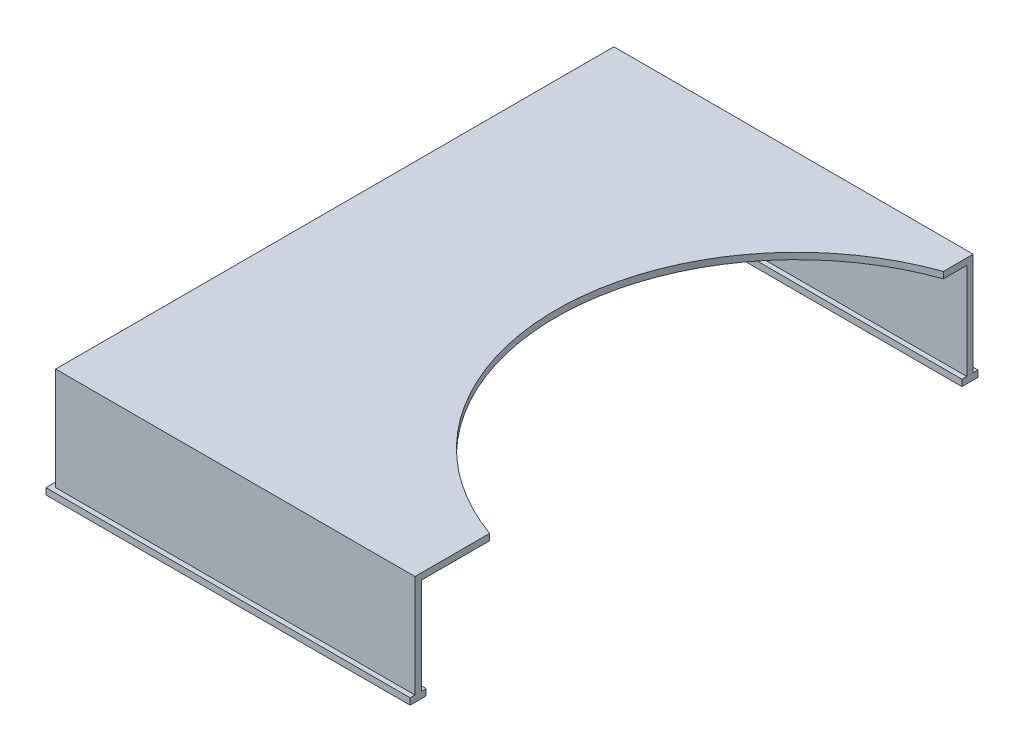
SolidWorks part; units mm, degrees
ref_plane "前视基准面" through (0, 0, 0) normal (0, 0, 1) x (1, 0, 0)
ref_plane "上视基准面" through (0, 0, 0) normal (0, 1, 0) x (1, 0, 0)
ref_plane "右视基准面" through (0, 0, 0) normal (1, 0, 0) x (0, 0, -1)
other "Configuration Table"
sketch "草图1" plane through (0, 0, 0) normal (0, 1, 0) x (1, 0, 0)
  line L1 (0, 0) -> (220, 0)
  line L2 (0, 0) -> (0, -170)
  line L3 (0, -170) -> (220, -170)
  line L4 (220, 0) -> (220, -170)
  line L9 (-2, 2) -> (222, 2)
  line L10 (-2, 2) -> (-2, -172)
  line L11 (-2, -172) -> (222, -172)
  line L12 (222, 2) -> (222, -172)
  point P4 (-2, 0)
  point P5 (0, 2)
  point P7 (222, -170)
  point P8 (220, -172)
  dimension "D1" = 220
  dimension "D2" = 170
  dimension "D3" = 2
  dimension "D4" = 2
  dimension "D5" = 2
  dimension "D6" = 2
extrude "凸台-拉伸1" add sketch "草图1" along normal blind 32
sketch "草图2" plane through (0, 0, 0) normal (0, 1, 0) x (1, 0, 0)
  line L0 (220, -170) -> (220, 0) construction
  line L1 (0, -170) -> (220, -170) construction
  line L2 (0, 0) -> (0, -170) construction
  line L3 (220, 0) -> (0, 0) construction
  line L14 (-3.5, 3.5) -> (223.5, 3.5)
  line L15 (-3.5, 3.5) -> (-3.5, -173.5)
  line L16 (-3.5, -173.5) -> (223.5, -173.5)
  line L17 (223.5, 3.5) -> (223.5, -173.5)
  line L18 (218.5, -168.5) -> (1.5, -168.5)
  line L19 (218.5, -168.5) -> (218.5, -1.5)
  line L20 (218.5, -1.5) -> (1.5, -1.5)
  line L21 (1.5, -168.5) -> (1.5, -1.5)
  point P0 (-3.5, 2)
  point P1 (-2, 3.5)
  point P2 (222, -173.5)
  point P3 (223.5, -172)
  point P4 (220, -168.5)
  point P5 (218.5, -170)
  point P8 (0, -1.5)
  point P11 (1.5, 0)
  point P14 (0, 0)
  point P17 (220, -170)
  point P18 (-2, 2)
  point P19 (222, -172)
  dimension "D1" = 1.5
  dimension "D2" = 1.5
  dimension "D3" = 1.5
  dimension "D4" = 1.5
  dimension "D5" = 1.5
  dimension "D6" = 1.5
  dimension "D7" = 1.5
  dimension "D8" = 1.5
extrude "凸台-拉伸2" add sketch "草图2" against normal blind 2
ref_plane "基准面1" through (0, 32, 0) normal (0, 1, 0) x (1, 0, 0)
sketch "草图3" plane through (0, 32, 0) normal (0, 1, 0) x (1, 0, 0)
  line L0 (-2, 2) -> (-2, -172) construction
  line L1 (222, -172) -> (222, 2) construction
  line L7 (-2, 2) -> (220, 2)
  line L8 (-2, 2) -> (-2, -170)
  line L9 (-2, -170) -> (220, -170)
  line L10 (220, 2) -> (220, -170)
  circle A0 centre (135, -78) radius 75
  point P0 (-2, -78)
  point P1 (222, -78)
  point P5 (210, -78)
  point P8 (60, -78)
  point P9 (135, -78)
  dimension "D1" = 80
  dimension "D2" = 12
  dimension "D3" = 62
  dimension "D4" = 75
extrude "凸台-拉伸3" add sketch "草图3" against normal blind 2
sketch "草图4" plane through (0, 32, 0) normal (0, 1, 0) x (1, 0, 0)
  line L0 (223.5, 3.5) -> (-3.5, 3.5) construction
  line L2 (110, 3.5) -> (223.5, 3.5)
  line L3 (110, 3.5) -> (110, -173.5)
  line L4 (110, -173.5) -> (223.5, -173.5)
  line L5 (223.5, 3.5) -> (223.5, -173.5)
  point P0 (110, 3.5)
extrude "切除-拉伸1" cut sketch "草图4" against normal through all
